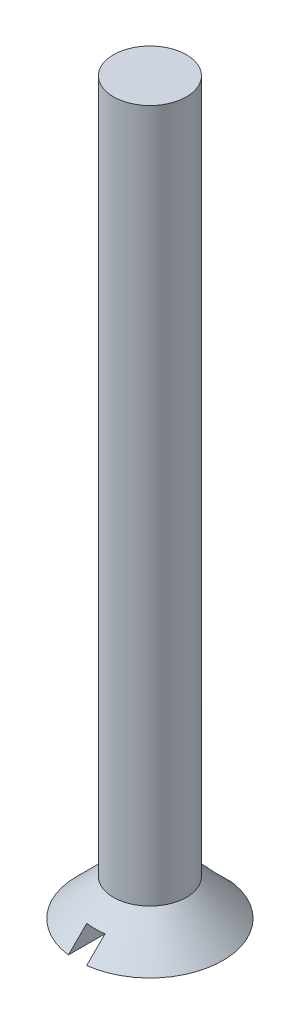
SolidWorks part; units mm, degrees
ref_plane "Front" through (0, 0, 0) normal (0, 0, 1) x (1, 0, 0)
ref_plane "Top" through (0, 0, 0) normal (0, 1, 0) x (1, 0, 0)
ref_plane "Right" through (0, 0, 0) normal (1, 0, 0) x (0, 0, -1)
sketch "Sketch1" plane through (0, 0, 0) normal (0, 0, 1) x (1, 0, 0)
  line L0 (0, 20) -> (0, 0)
  line L1 (0, 0) -> (-2, 0)
  line L2 (-2, 0) -> (-1, 1)
  line L3 (-1, 1) -> (-1, 20)
  line L4 (-1, 20) -> (0, 20)
  dimension "D1" = 20
  dimension "D2" = 1
  dimension "D3" = 45
  dimension "D4" = 2
revolve "Revolve1" add sketch "Sketch1" angle 360 about L0
sketch "Sketch2" plane through (0, 0, 0) normal (0, -1, 0) x (1, 0, 0)
  line L0 (0.25, 2) -> (0.25, -2)
  line L1 (0.25, -2) -> (-0.25, -2)
  line L2 (-0.25, -2) -> (-0.25, 2)
  line L3 (-0.25, 2) -> (0.25, 2)
  circle A1 centre (0, 0) radius 2 construction
  dimension "D1" = 0.25
  dimension "D2" = 0.25
extrude "Cut-Extrude1" cut sketch "Sketch2" against normal blind 0.5
